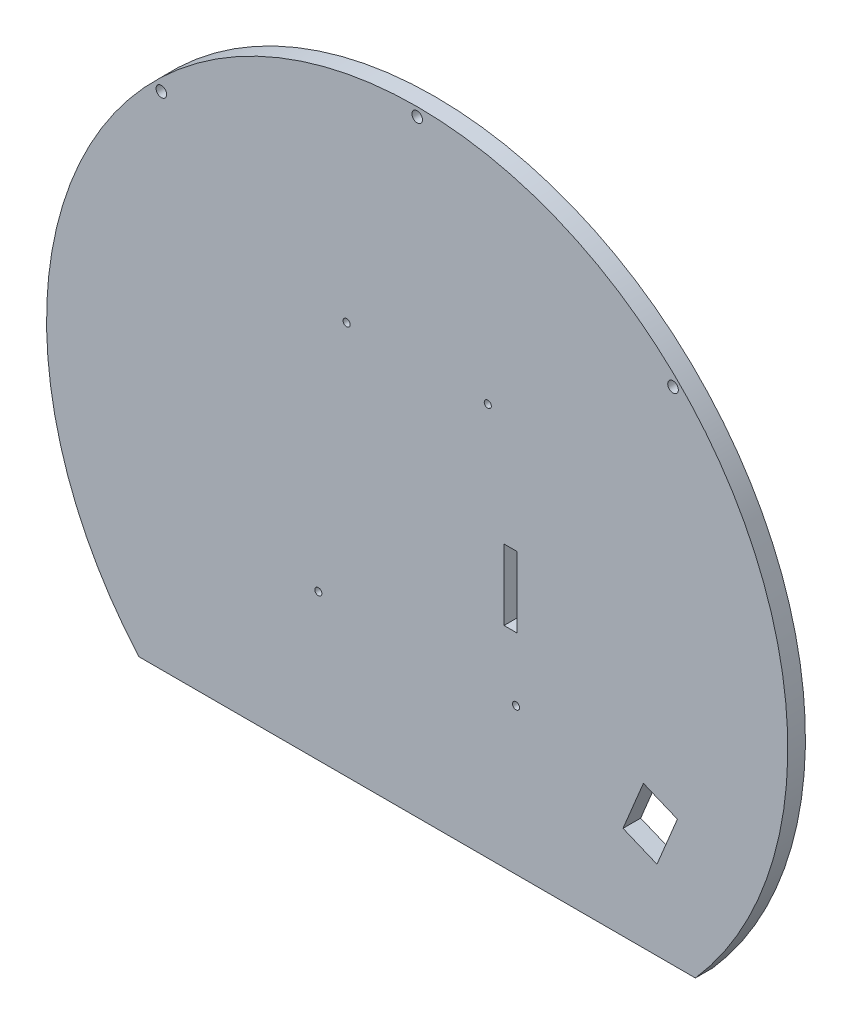
SolidWorks part; units mm, degrees
ref_plane "Plan de face" through (0, 0, 0) normal (0, 0, 1) x (1, 0, 0)
ref_plane "Plan de dessus" through (0, 0, 0) normal (0, 1, 0) x (1, 0, 0)
ref_plane "Plan de droite" through (0, 0, 0) normal (1, 0, 0) x (0, 0, -1)
sketch "Esquisse1" plane through (0, 0, 0) normal (0, 0, 1) x (1, 0, 0)
  line L0 (78.8107, -69.3821) -> (-78.8107, -69.3821)
  arc A1 (78.8107, -69.3821) -> (-78.8107, -69.3821) centre (0, 0) ccw
extrude "Boss.-Extru.1" add sketch "Esquisse1" along normal blind 5
sketch "Esquisse2" plane through (0, 0, 5) normal (0, 0, 1) x (1, 0, 0)
  circle A0 centre (0, 102.5) radius 1.5
  circle A1 centre (72.4784, 72.4784) radius 1.5
  circle A2 centre (-72.4784, 72.4784) radius 1.5
extrude "Enlèv. mat.-Extru.1" cut sketch "Esquisse2" against normal blind 5
sketch "Esquisse3" plane through (0, 0, 5) normal (0, 0, 1) x (1, 0, 0)
  circle A0 centre (20, 42) radius 1
  circle A1 centre (-20, 42) radius 1
  circle A2 centre (-28, -28) radius 1
  circle A3 centre (28, -28) radius 1
extrude "Enlèv. mat.-Extru.2" cut sketch "Esquisse3" against normal through all
sketch "Esquisse4" plane through (0, 0, 5) normal (0, 0, 1) x (1, 0, 0)
  line L0 (58.3125, -42.9161) -> (64.0966, -28.9678)
  line L1 (64.0966, -28.9678) -> (73.7218, -32.9591)
  line L2 (73.7218, -32.9591) -> (67.9378, -46.9074)
  line L3 (67.9378, -46.9074) -> (58.3125, -42.9161)
extrude "Enlèv. mat.-Extru.3" cut sketch "Esquisse4" against normal through all
sketch "Esquisse5" plane through (0, 0, 5) normal (0, 0, 1) x (1, 0, 0)
  line L1 (24.6, 10) -> (28.25, 10)
  line L2 (24.6, 10) -> (24.6, -10)
  line L3 (24.6, -10) -> (28.25, -10)
  line L4 (28.25, 10) -> (28.25, -10)
extrude "Enlèv. mat.-Extru.4" cut sketch "Esquisse5" against normal through all
